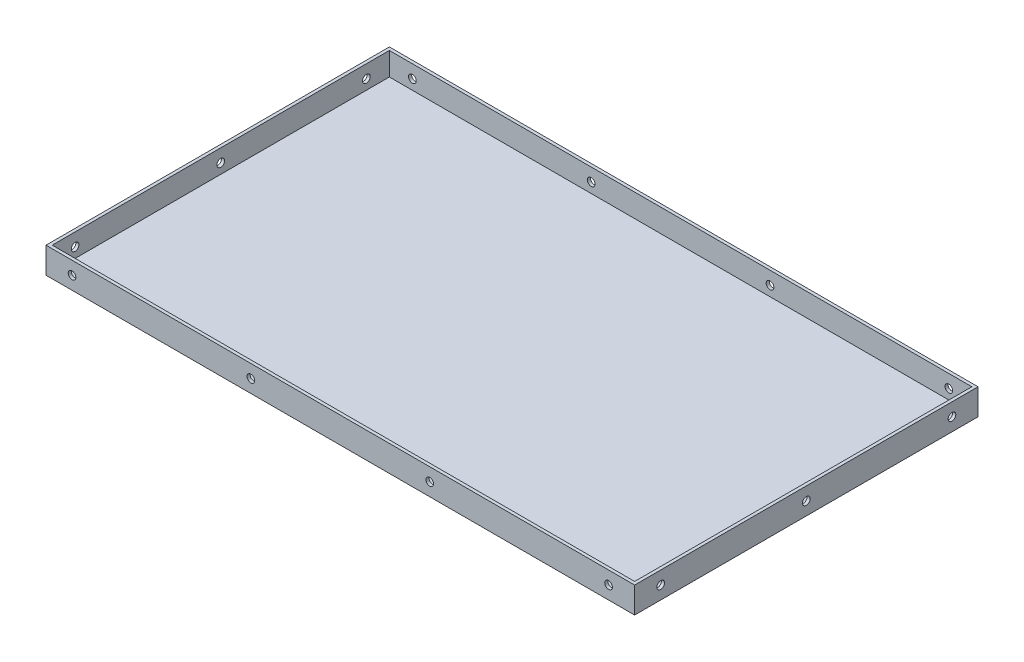
SolidWorks part; units mm, degrees
ref_plane "前视基准面" through (0, 0, 0) normal (0, 0, 1) x (1, 0, 0)
ref_plane "上视基准面" through (0, 0, 0) normal (0, 1, 0) x (1, 0, 0)
ref_plane "右视基准面" through (0, 0, 0) normal (1, 0, 0) x (0, 0, -1)
sketch "草图1" plane through (0, 0, 0) normal (0, 1, 0) x (1, 0, 0)
  line L1 (192, -112) -> (-192, -112)
  line L2 (192, -112) -> (192, 112)
  line L3 (192, 112) -> (-192, 112)
  line L4 (-192, -112) -> (-192, 112)
  line L5 (192, -112) -> (-192, 112) construction
  line L6 (192, 112) -> (-192, -112) construction
  point P0 (0, 0)
  dimension "D1" = 384
  dimension "D2" = 224
extrude "凸台-拉伸1" add sketch "草图1" along normal blind 2
sketch "草图2" plane through (0, 2, 0) normal (0, 1, 0) x (1, 0, 0)
  line L1 (-192, 112) -> (192, 112)
  line L2 (-192, 112) -> (-192, -112)
  line L3 (-192, -112) -> (192, -112)
  line L4 (192, 112) -> (192, -112)
  line L5 (-190, 110) -> (190, 110)
  line L6 (-190, 110) -> (-190, -110)
  line L7 (-190, -110) -> (190, -110)
  line L8 (190, 110) -> (190, -110)
  dimension "D1" = 2
  dimension "D2" = 2
  dimension "D3" = 2
  dimension "D4" = 2
extrude "凸台-拉伸2" add sketch "草图2" along normal blind 15
sketch "草图3" plane through (0, 0, -112) normal (0, 0, -1) x (-1, 0, 0)
  line L0 (-192, 17) -> (-192, 0) construction
  circle A0 centre (-175, 8.5) radius 2.5
  circle A1 centre (-58.33, 8.5) radius 2.5
  circle A2 centre (58.34, 8.5) radius 2.5
  circle A3 centre (175.01, 8.5) radius 2.5
  dimension "D1" = 5
  dimension "D2" = 17
  dimension "D3" = 4
extrude "切除-拉伸1" cut sketch "草图3" against normal through all
sketch "草图4" plane through (192, 0, 0) normal (1, 0, 0) x (0, 0, -1)
  line L0 (-112, 17) -> (-112, 0) construction
  circle A0 centre (-95, 8.5) radius 2.5
  circle A1 centre (0, 8.5) radius 2.5
  circle A2 centre (95, 8.5) radius 2.5
  dimension "D1" = 5
  dimension "D2" = 17
  dimension "D3" = 3
extrude "切除-拉伸2" cut sketch "草图4" against normal through all
